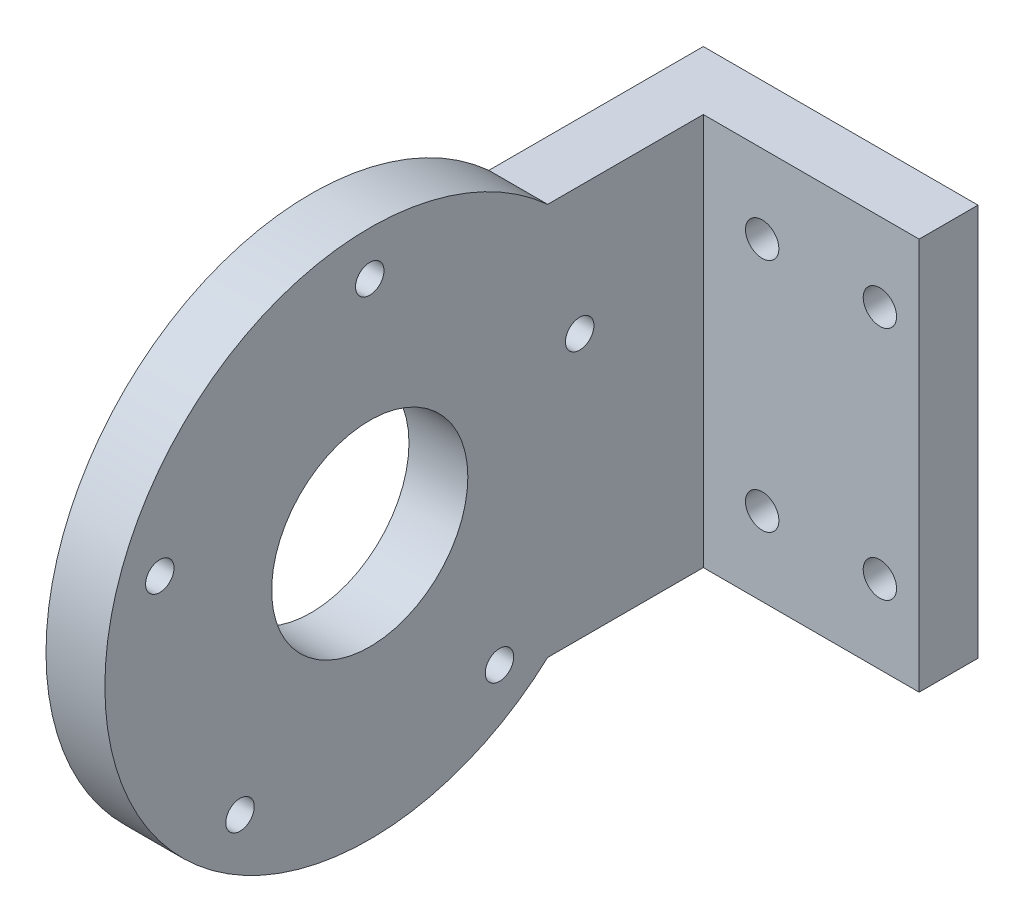
SolidWorks part; units mm, degrees
ref_plane "Front Plane" through (0, 0, 0) normal (0, 0, 1) x (1, 0, 0)
ref_plane "Top Plane" through (0, 0, 0) normal (0, 1, 0) x (1, 0, 0)
ref_plane "Right Plane" through (0, 0, 0) normal (1, 0, 0) x (0, 0, -1)
ref_plane "Plane1" through (221, 0, 0) normal (1, 0, 0) x (0, 0, -1)
sketch "Sketch1" plane through (221, 0, 0) normal (1, 0, 0) x (0, 0, -1)
  circle A0 centre (-300, 300) radius 27
extrude "Boss-Extrude1" add sketch "Sketch1" along normal blind 6
sketch "Sketch2" plane through (221, 0, 0) normal (1, 0, 0) x (0, 0, -1)
  line L0 (-260, 280) -> (-285, 280)
  line L1 (-285, 280) -> (-285, 320)
  line L2 (-285, 320) -> (-260, 320)
  line L3 (-260, 320) -> (-260, 280)
extrude "Boss-Extrude2" add sketch "Sketch2" along normal blind 6
sketch "Sketch3" plane through (221, 0, 0) normal (1, 0, 0) x (0, 0, -1)
  circle A0 centre (-300, 300) radius 10
  circle A1 centre (-300, 322.5) radius 1.45
  circle A2 centre (-278.6012, 306.9529) radius 1.45
  circle A3 centre (-286.7748, 281.7971) radius 1.45
  circle A4 centre (-313.2252, 281.7971) radius 1.45
  circle A5 centre (-321.3988, 306.9529) radius 1.45
extrude "Cut-Extrude1" cut sketch "Sketch3" along normal blind 6.01
ref_plane "Plane2" through (0, 0, 260) normal (0, 0, 1) x (1, 0, 0)
sketch "Sketch4" plane through (0, 0, 260) normal (0, 0, 1) x (1, 0, 0)
  line L0 (226.99, 280) -> (249, 280)
  line L1 (249, 280) -> (249, 320)
  line L2 (249, 320) -> (226.99, 320)
  line L3 (226.99, 320) -> (226.99, 280)
  circle A0 centre (233, 288) radius 1.7
  circle A1 centre (233, 312) radius 1.7
  circle A2 centre (245, 288) radius 1.7
  circle A3 centre (245, 312) radius 1.7
extrude "Boss-Extrude3" add sketch "Sketch4" along normal blind 6
